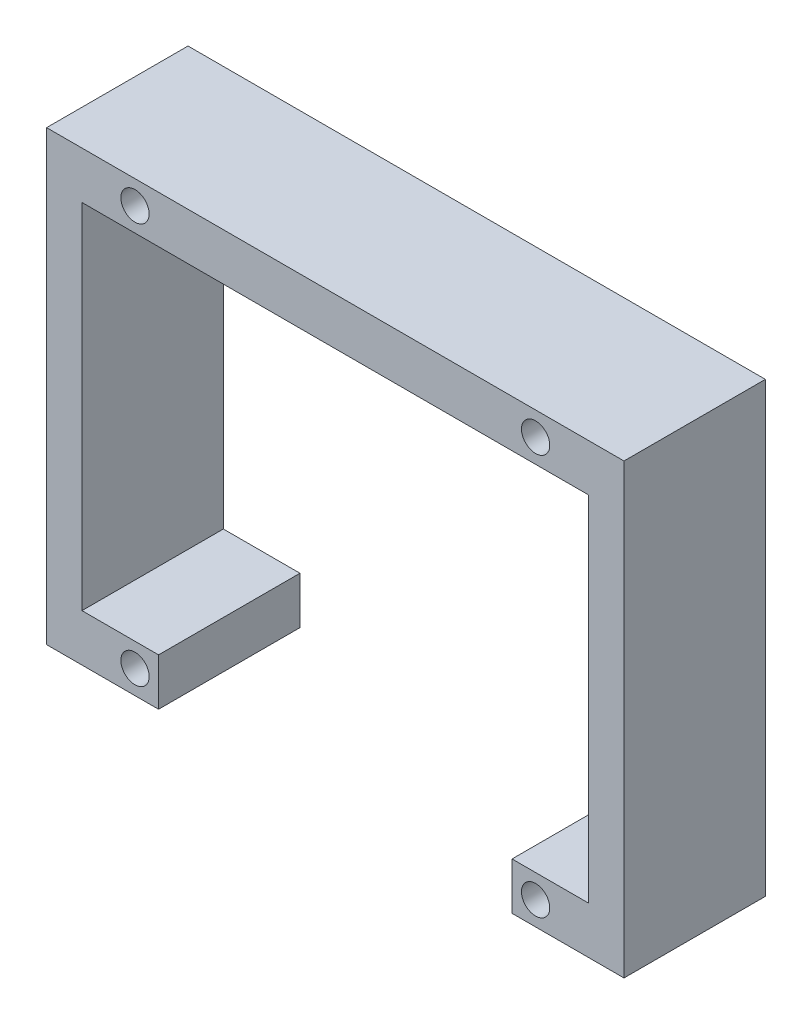
SolidWorks part; units mm, degrees
ref_plane "前视基准面" through (0, 0, 0) normal (0, 0, 1) x (1, 0, 0)
ref_plane "上视基准面" through (0, 0, 0) normal (0, 1, 0) x (1, 0, 0)
ref_plane "右视基准面" through (0, 0, 0) normal (1, 0, 0) x (0, 0, -1)
other "Configuration Table"
sketch "草图1" plane through (0, 0, 0) normal (0, 0, 1) x (1, 0, 0)
  line L0 (-15, -19) -> (-15, -15)
  line L1 (17, -17) -> (-17, -17) construction
  line L2 (17, -17) -> (17, 17) construction
  line L3 (17, 17) -> (-17, 17) construction
  line L4 (-17, -17) -> (-17, 17) construction
  line L5 (17, -17) -> (-17, 17) construction
  line L6 (17, 17) -> (-17, -17) construction
  line L7 (-15, -15) -> (-21.5, -15)
  line L8 (-21.5, -15) -> (-21.5, 15)
  line L9 (-21.5, 15) -> (21.5, 15)
  line L10 (21.5, 15) -> (21.5, -15)
  line L11 (21.5, -15) -> (15, -15)
  line L12 (15, -15) -> (15, -19)
  line L13 (15, -19) -> (24.5, -19)
  line L14 (24.5, -19) -> (24.5, 19)
  line L15 (24.5, 19) -> (-24.5, 19)
  line L16 (-24.5, 19) -> (-24.5, -19)
  line L17 (-24.5, -19) -> (-15, -19)
  line L18 (0, 0) -> (0, 11.7421) construction
  line L19 (0, 0) -> (13.3036, 0) construction
  circle A0 centre (-17, 17) radius 1.2
  circle A1 centre (17, 17) radius 1.2
  circle A2 centre (-17, -17) radius 1.2
  circle A3 centre (17, -17) radius 1.2
  point P0 (0, 0)
  point P24 (0, 19)
  point P26 (0, 15)
  dimension "D2" = 2.4
  dimension "D1" = 34
  dimension "D3" = 2
  dimension "D4" = 2
  dimension "D5" = 2
  dimension "D7" = 2
  dimension "D8" = 2
  dimension "D9" = 43
  dimension "D10" = 3
  dimension "D11" = 2
  dimension "D12" = 2
extrude "凸台-拉伸1" add sketch "草图1" along normal blind 12
